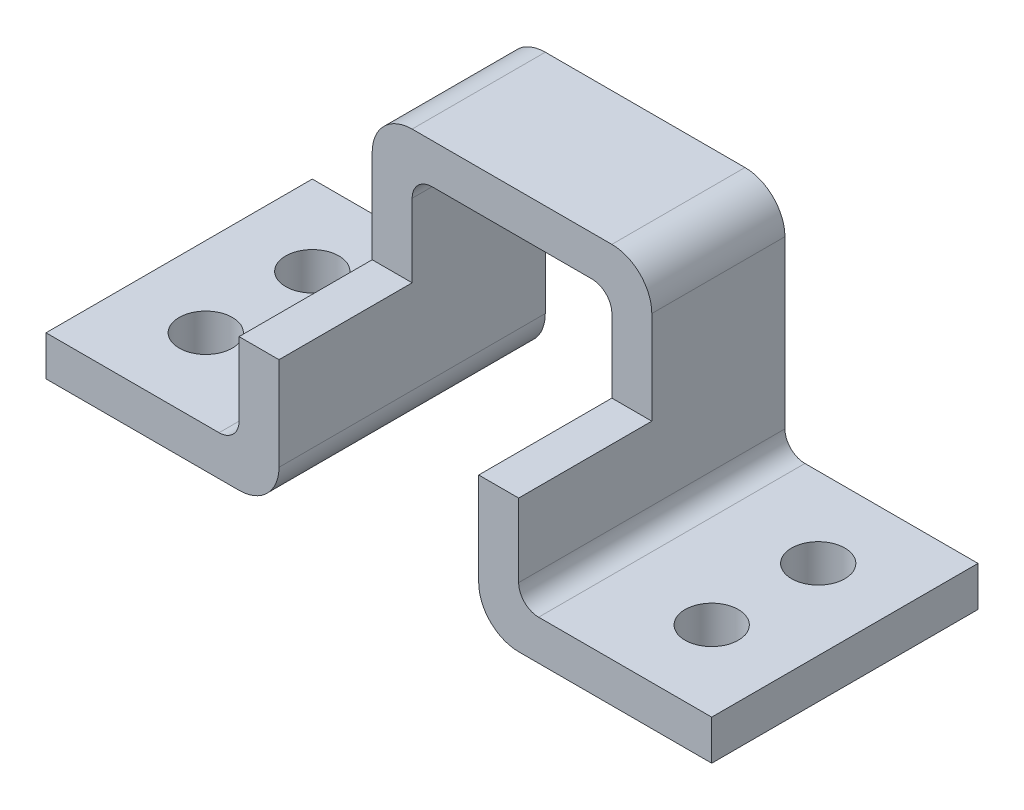
SolidWorks part; units mm, degrees
ref_plane "Front Plane" through (0, 0, 0) normal (0, 0, 1) x (1, 0, 0)
ref_plane "Top Plane" through (0, 0, 0) normal (0, 1, 0) x (1, 0, 0)
ref_plane "Right Plane" through (0, 0, 0) normal (1, 0, 0) x (0, 0, -1)
sketch "Sketch1" plane through (0, 0, 0) normal (0, 0, 1) x (1, 0, 0)
  line L0 (0, 6) -> (0, 0)
  line L6 (100, 0) -> (100, 6)
  line L12 (0, 0) -> (29, 0)
  line L13 (35, 6) -> (35, 31)
  line L14 (38, 34) -> (62, 34)
  line L15 (65, 31) -> (65, 6)
  line L16 (71, 0) -> (100, 0)
  line L17 (100, 6) -> (74, 6)
  line L18 (71, 9) -> (71, 34)
  line L19 (65, 40) -> (35, 40)
  line L20 (29, 34) -> (29, 9)
  line L21 (26, 6) -> (0, 6)
  arc A0 (29, 34) -> (35, 40) centre (35, 34) cw
  arc A1 (35, 31) -> (38, 34) centre (38, 31) cw
  arc A2 (26, 6) -> (29, 9) centre (26, 9) ccw
  arc A3 (65, 31) -> (62, 34) centre (62, 31) ccw
  arc A4 (74, 6) -> (71, 9) centre (74, 9) cw
  arc A5 (71, 0) -> (65, 6) centre (71, 6) cw
  arc A6 (71, 34) -> (65, 40) centre (65, 34) ccw
  arc A7 (29, 0) -> (35, 6) centre (29, 6) ccw
  point P28 (0, 0)
  dimension "D3" = 6
  dimension "D4" = 6
  dimension "D5" = 100
  dimension "D6" = 40
  dimension "D7" = 35
  dimension "D8" = 65
  dimension "D9" = 6
  dimension "D10" = 3
  dimension "D1" = 6
  dimension "D2" = 6
extrude "Boss-Extrude1" add sketch "Sketch1" along normal blind 40
sketch "Sketch2" plane through (0, 0, 40) normal (0, 0, 1) x (1, 0, 0)
  line L0 (29, 20) -> (35, 20)
  line L1 (65, 31) -> (65, 20)
  line L2 (35, 6) -> (35, 31) construction
  line L3 (65, 20) -> (71, 20)
  line L4 (71, 34) -> (71, 20)
  line L7 (29, 34) -> (29, 9) construction
  line L10 (0, 0) -> (29, 0) construction
  line L11 (71, 9) -> (71, 34) construction
  line L12 (65, 31) -> (65, 6) construction
  line L13 (35, 31) -> (35, 20)
  line L14 (29, 20) -> (29, 34)
  line L15 (35, 40) -> (65, 40)
  line L16 (38, 34) -> (62, 34)
  arc A0 (29, 34) -> (35, 40) centre (35, 34) cw
  arc A1 (35, 40) -> (29, 34) centre (35, 34) ccw construction
  arc A2 (35, 31) -> (38, 34) centre (38, 31) cw
  arc A3 (38, 34) -> (35, 31) centre (38, 31) ccw construction
  arc A4 (65, 40) -> (71, 34) centre (65, 34) cw
  arc A5 (71, 34) -> (65, 40) centre (65, 34) ccw construction
  arc A6 (62, 34) -> (65, 31) centre (62, 31) cw
  arc A7 (65, 31) -> (62, 34) centre (62, 31) ccw construction
  dimension "D1" = 20
extrude "Cut-Extrude1" cut sketch "Sketch2" against normal blind 20
sketch "Sketch3" plane through (0, 6, 0) normal (0, 1, 0) x (1, 0, 0)
  line L0 (26, -40) -> (0, -40) construction
  line L1 (0, -40) -> (0, 0) construction
  line L2 (100, -40) -> (100, 0) construction
  circle A0 centre (12, -12) radius 4
  circle A1 centre (12, -28) radius 4
  circle A2 centre (88, -12) radius 4
  circle A3 centre (88, -28) radius 4
  point P4 (13.8654, -21.0423)
  point P7 (88.2193, -9.7503)
  point P10 (88.2193, -21.0423)
  point P11 (13.8654, -9.7503)
  point P16 (0, 0)
  point P17 (0, 0)
  point P18 (0, 0)
  point P19 (0, 0)
  point P20 (0, 0)
  dimension "D1" = 8
  dimension "D2" = 16
  dimension "D3" = 12
  dimension "D4" = 12
  dimension "D5" = 12
extrude "Cut-Extrude2" cut sketch "Sketch3" against normal up to next
